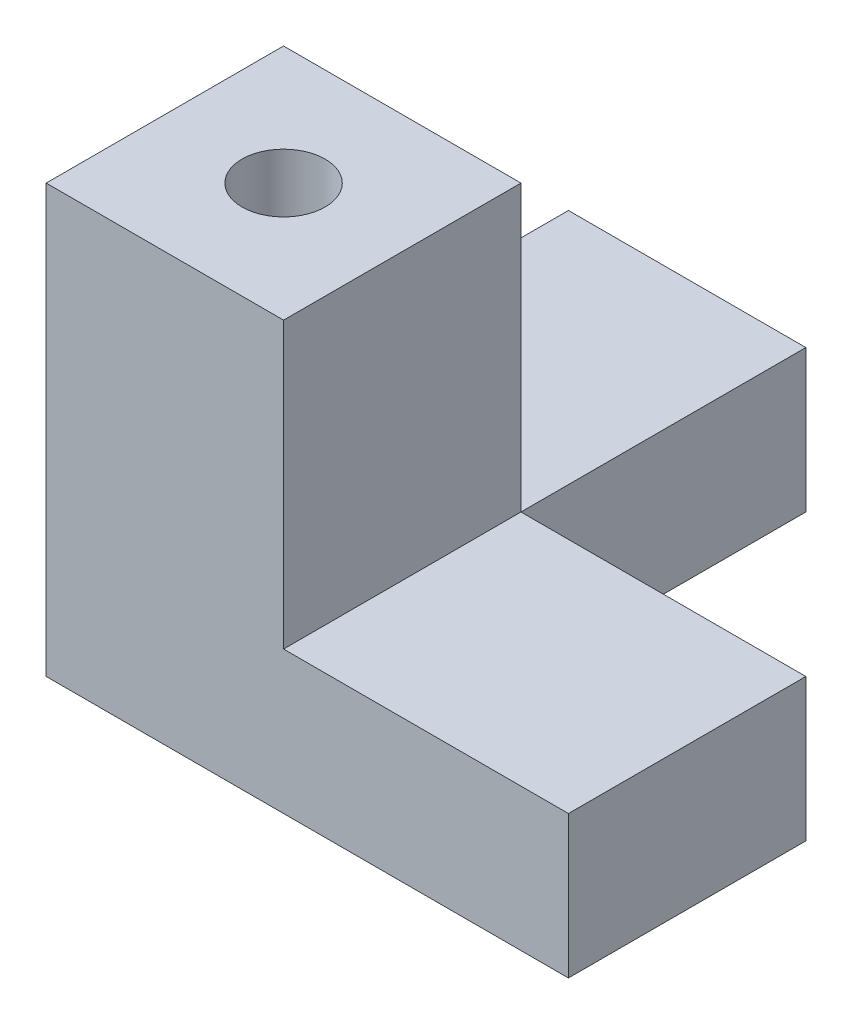
SolidWorks part; units mm, degrees
ref_plane "Front Plane" through (0, 0, 0) normal (0, 0, 1) x (1, 0, 0)
ref_plane "Top Plane" through (0, 0, 0) normal (0, 1, 0) x (1, 0, 0)
ref_plane "Right Plane" through (0, 0, 0) normal (1, 0, 0) x (0, 0, -1)
sketch "Sketch1" plane through (0, 0, 0) normal (0, 1, 0) x (1, 0, 0)
  line L0 (0, 0) -> (0, 22)
  line L1 (0, 22) -> (10, 22)
  line L2 (10, 22) -> (10, 10)
  line L3 (10, 10) -> (22, 10)
  line L4 (22, 10) -> (22, 0)
  line L5 (22, 0) -> (0, 0)
  dimension "D1" = 12
  dimension "D2" = 12
  dimension "D3" = 10
  dimension "D4" = 10
extrude "Boss-Extrude1" add sketch "Sketch1" along normal blind 6
sketch "Sketch2" plane through (0, 6, 0) normal (0, 1, 0) x (1, 0, 0)
  line L1 (10, 10) -> (0, 10)
  line L2 (10, 10) -> (10, 0)
  line L3 (10, 0) -> (0, 0)
  line L4 (0, 10) -> (0, 0)
extrude "Boss-Extrude2" add sketch "Sketch2" along normal blind 12
sketch "Sketch3" plane through (0, 18, 0) normal (0, 1, 0) x (1, 0, 0)
  line L0 (0, 0) -> (10, 10) construction
  circle A0 centre (5, 5) radius 1.75
  dimension "D1" = 3.5
extrude "Cut-Extrude1" cut sketch "Sketch3" against normal through all
sketch "Sketch4" plane through (0, 0, 0) normal (0, -1, 0) x (1, 0, 0)
  line L0 (5, -5) -> (1.8246, -5) construction
  line L1 (1.8246, -5) -> (3.4123, -7.75)
  line L2 (3.4123, -7.75) -> (6.5877, -7.75)
  line L3 (6.5877, -7.75) -> (8.1754, -5)
  line L4 (8.1754, -5) -> (6.5877, -2.25)
  line L5 (6.5877, -2.25) -> (3.4123, -2.25)
  line L6 (3.4123, -2.25) -> (1.8246, -5)
  circle A0 centre (5, -5) radius 2.75 construction
  dimension "D1" = 5.5
extrude "Cut-Extrude2" cut sketch "Sketch4" against normal blind 3
